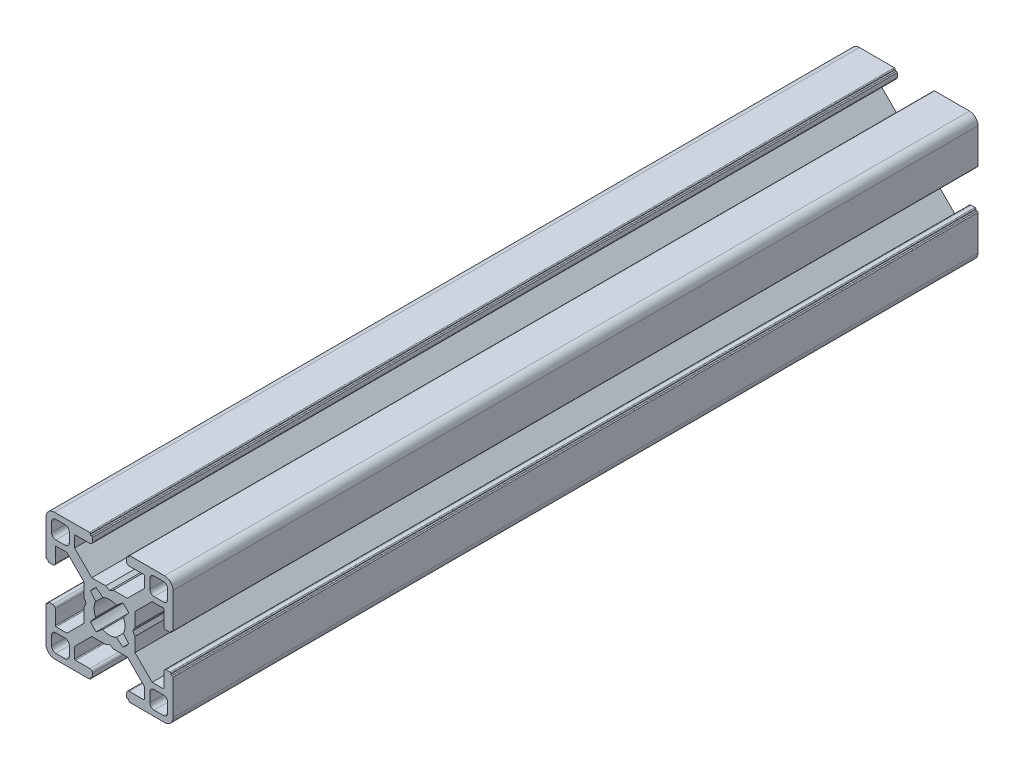
SolidWorks part; units mm, degrees
ref_plane "Front" through (0, 0, 0) normal (0, 0, 1) x (1, 0, 0)
ref_plane "Top" through (0, 0, 0) normal (0, 1, 0) x (1, 0, 0)
ref_plane "Right" through (0, 0, 0) normal (1, 0, 0) x (0, 0, -1)
sketch "Sketch1" plane through (0, 0, 0) normal (0, 0, 1) x (1, 0, 0)
  line L0 (13.7, 12.7) -> (13.7, 10.5)
  line L1 (10.5, 9.5) -> (12.7, 9.5)
  line L2 (9.5, 12.7) -> (9.5, 10.5)
  line L3 (10.5, 13.7) -> (12.7, 13.7)
  line L4 (3.1359, 4.5184) -> (1.6001, 3.2806)
  line L5 (3.2806, 1.6001) -> (4.5053, 3.1547)
  line L6 (6.0045, 0.9) -> (5.4849, 0)
  line L7 (6.0045, 4.2045) -> (6.0045, 0.9)
  line L8 (0, -5.4849) -> (0.9, -6)
  line L9 (0.9, -6) -> (4.2045, -6)
  line L10 (4.2045, -6) -> (8.25, -10.05)
  line L11 (8.25, -10.05) -> (8.25, -12.6)
  line L12 (4.65, -12.8) -> (8.05, -12.8)
  line L13 (4.05, -14.3) -> (4.05, -13.4)
  line L14 (4.25, -14.5) -> (4.35, -14.5)
  line L15 (4.55, -14.8) -> (4.55, -14.7)
  line L16 (4.75, -15) -> (13, -15)
  line L17 (15, -13) -> (15, -4.75)
  line L18 (14.7, -4.55) -> (14.8, -4.55)
  line L19 (14.5, -4.35) -> (14.5, -4.25)
  line L20 (13.4, -4.05) -> (14.3, -4.05)
  line L21 (12.8, -8.05) -> (12.8, -4.65)
  line L22 (12.6, -8.25) -> (10.05, -8.25)
  line L23 (10.05, -8.25) -> (6.0045, -4.2045)
  line L24 (6.0045, -4.2045) -> (6.0045, -0.9)
  line L25 (6.0045, -0.9) -> (5.4849, 0)
  line L26 (10.05, 8.25) -> (6.0045, 4.2045)
  line L27 (12.6, 8.25) -> (10.05, 8.25)
  line L28 (12.8, 8.05) -> (12.8, 4.65)
  line L29 (13.4, 4.05) -> (14.3, 4.05)
  line L30 (14.5, 4.35) -> (14.5, 4.25)
  line L31 (14.7, 4.55) -> (14.8, 4.55)
  line L32 (15, 13) -> (15, 4.75)
  line L33 (4.75, 15) -> (13, 15)
  line L34 (4.55, 14.8) -> (4.55, 14.7)
  line L35 (4.25, 14.5) -> (4.35, 14.5)
  line L36 (4.05, 14.3) -> (4.05, 13.4)
  line L37 (4.65, 12.8) -> (8.05, 12.8)
  line L38 (8.25, 10.05) -> (8.25, 12.6)
  line L39 (4.2045, 6) -> (8.25, 10.05)
  line L40 (0.9, 6) -> (4.2045, 6)
  line L41 (0, 5.4849) -> (0.9, 6)
  line L42 (-13.7, -12.7) -> (-13.7, -10.5)
  line L43 (-10.5, -9.5) -> (-12.7, -9.5)
  line L44 (-9.5, -12.7) -> (-9.5, -10.5)
  line L45 (-10.5, -13.7) -> (-12.7, -13.7)
  line L46 (-3.1359, -4.5184) -> (-1.6001, -3.2806)
  line L47 (-3.2806, -1.6001) -> (-4.5053, -3.1547)
  line L48 (0, 5.4849) -> (-0.9, 6)
  line L49 (-0.9, 6) -> (-4.2045, 6)
  line L50 (-4.2045, 6) -> (-8.25, 10.05)
  line L51 (-8.25, 10.05) -> (-8.25, 12.6)
  line L52 (-4.65, 12.8) -> (-8.05, 12.8)
  line L53 (-4.05, 14.3) -> (-4.05, 13.4)
  line L54 (-4.25, 14.5) -> (-4.35, 14.5)
  line L55 (-4.55, 14.8) -> (-4.55, 14.7)
  line L56 (-4.75, 15) -> (-13, 15)
  line L57 (-15, 13) -> (-15, 4.75)
  line L58 (-14.7, 4.55) -> (-14.8, 4.55)
  line L59 (-14.5, 4.35) -> (-14.5, 4.25)
  line L60 (-13.4, 4.05) -> (-14.3, 4.05)
  line L61 (-12.8, 8.05) -> (-12.8, 4.65)
  line L62 (-12.6, 8.25) -> (-10.05, 8.25)
  line L63 (-10.05, 8.25) -> (-6.0045, 4.2045)
  line L64 (-6.0045, -0.9) -> (-5.4849, 0)
  line L65 (-6.0045, -4.2045) -> (-6.0045, -0.9)
  line L66 (-10.05, -8.25) -> (-6.0045, -4.2045)
  line L67 (-12.6, -8.25) -> (-10.05, -8.25)
  line L68 (-12.8, -8.05) -> (-12.8, -4.65)
  line L69 (-13.4, -4.05) -> (-14.3, -4.05)
  line L70 (-14.5, -4.35) -> (-14.5, -4.25)
  line L71 (-14.7, -4.55) -> (-14.8, -4.55)
  line L72 (-15, -13) -> (-15, -4.75)
  line L73 (-4.75, -15) -> (-13, -15)
  line L74 (-4.55, -14.8) -> (-4.55, -14.7)
  line L75 (-4.25, -14.5) -> (-4.35, -14.5)
  line L76 (-4.05, -14.3) -> (-4.05, -13.4)
  line L77 (3.2806, -1.6001) -> (4.5053, -3.1547)
  line L78 (3.1359, -4.5184) -> (1.6001, -3.2806)
  line L79 (-4.65, -12.8) -> (-8.05, -12.8)
  line L80 (-8.25, -10.05) -> (-8.25, -12.6)
  line L81 (-4.2045, -6) -> (-8.25, -10.05)
  line L82 (-0.9, -6) -> (-4.2045, -6)
  line L83 (0, -5.4849) -> (-0.9, -6)
  line L84 (10.5, -13.7) -> (12.7, -13.7)
  line L85 (9.5, -12.7) -> (9.5, -10.5)
  line L86 (10.5, -9.5) -> (12.7, -9.5)
  line L87 (13.7, -12.7) -> (13.7, -10.5)
  line L88 (-6.0045, 4.2045) -> (-6.0045, 0.9)
  line L89 (-6.0045, 0.9) -> (-5.4849, 0)
  line L90 (-3.2806, 1.6001) -> (-4.5053, 3.1547)
  line L91 (-3.1359, 4.5184) -> (-1.6001, 3.2806)
  line L92 (-10.5, 13.7) -> (-12.7, 13.7)
  line L93 (-9.5, 12.7) -> (-9.5, 10.5)
  line L94 (-10.5, 9.5) -> (-12.7, 9.5)
  line L95 (-13.7, 12.7) -> (-13.7, 10.5)
  line L96 (-23.4857, 0) -> (20.9308, 0) construction
  line L97 (0, 17.9563) -> (0, -17.361) construction
  arc A0 (13.7, 12.7) -> (12.7, 13.7) centre (12.7, 12.7) ccw
  arc A1 (12.7, 9.5) -> (13.7, 10.5) centre (12.7, 10.5) ccw
  arc A2 (9.5, 10.5) -> (10.5, 9.5) centre (10.5, 10.5) ccw
  arc A3 (10.5, 13.7) -> (9.5, 12.7) centre (10.5, 12.7) ccw
  arc A4 (1.6001, 3.2806) -> (-1.6001, 3.2806) centre (0, 0) ccw
  arc A5 (8.25, -12.6) -> (8.05, -12.8) centre (8.05, -12.6) cw
  arc A6 (4.65, -12.8) -> (4.05, -13.4) centre (4.65, -13.4) ccw
  arc A7 (4.05, -14.3) -> (4.25, -14.5) centre (4.25, -14.3) ccw
  arc A8 (4.35, -14.5) -> (4.55, -14.7) centre (4.35, -14.7) cw
  arc A9 (4.55, -14.8) -> (4.75, -15) centre (4.75, -14.8) ccw
  arc A10 (13, -15) -> (15, -13) centre (13, -13) ccw
  arc A11 (15, -4.75) -> (14.8, -4.55) centre (14.8, -4.75) ccw
  arc A12 (14.7, -4.55) -> (14.5, -4.35) centre (14.7, -4.35) cw
  arc A13 (14.5, -4.25) -> (14.3, -4.05) centre (14.3, -4.25) ccw
  arc A14 (13.4, -4.05) -> (12.8, -4.65) centre (13.4, -4.65) ccw
  arc A15 (12.8, -8.05) -> (12.6, -8.25) centre (12.6, -8.05) cw
  arc A16 (4.5053, 3.1547) -> (3.1359, 4.5184) centre (0, 0) ccw
  arc A17 (12.8, 8.05) -> (12.6, 8.25) centre (12.6, 8.05) ccw
  arc A18 (13.4, 4.05) -> (12.8, 4.65) centre (13.4, 4.65) cw
  arc A19 (14.5, 4.25) -> (14.3, 4.05) centre (14.3, 4.25) cw
  arc A20 (14.7, 4.55) -> (14.5, 4.35) centre (14.7, 4.35) ccw
  arc A21 (15, 4.75) -> (14.8, 4.55) centre (14.8, 4.75) cw
  arc A22 (13, 15) -> (15, 13) centre (13, 13) cw
  arc A23 (4.55, 14.8) -> (4.75, 15) centre (4.75, 14.8) cw
  arc A24 (4.35, 14.5) -> (4.55, 14.7) centre (4.35, 14.7) ccw
  arc A25 (4.05, 14.3) -> (4.25, 14.5) centre (4.25, 14.3) cw
  arc A26 (4.65, 12.8) -> (4.05, 13.4) centre (4.65, 13.4) cw
  arc A27 (8.25, 12.6) -> (8.05, 12.8) centre (8.05, 12.6) ccw
  arc A28 (-13.7, -12.7) -> (-12.7, -13.7) centre (-12.7, -12.7) ccw
  arc A29 (-12.7, -9.5) -> (-13.7, -10.5) centre (-12.7, -10.5) ccw
  arc A30 (-9.5, -10.5) -> (-10.5, -9.5) centre (-10.5, -10.5) ccw
  arc A31 (-10.5, -13.7) -> (-9.5, -12.7) centre (-10.5, -12.7) ccw
  arc A32 (-4.5053, -3.1547) -> (-3.1359, -4.5184) centre (0, 0) ccw
  arc A33 (-3.2806, 1.6001) -> (-3.2806, -1.6001) centre (0, 0) ccw
  arc A34 (-8.25, 12.6) -> (-8.05, 12.8) centre (-8.05, 12.6) cw
  arc A35 (-4.65, 12.8) -> (-4.05, 13.4) centre (-4.65, 13.4) ccw
  arc A36 (-4.05, 14.3) -> (-4.25, 14.5) centre (-4.25, 14.3) ccw
  arc A37 (-4.35, 14.5) -> (-4.55, 14.7) centre (-4.35, 14.7) cw
  arc A38 (-4.55, 14.8) -> (-4.75, 15) centre (-4.75, 14.8) ccw
  arc A39 (-13, 15) -> (-15, 13) centre (-13, 13) ccw
  arc A40 (-15, 4.75) -> (-14.8, 4.55) centre (-14.8, 4.75) ccw
  arc A41 (-14.7, 4.55) -> (-14.5, 4.35) centre (-14.7, 4.35) cw
  arc A42 (-14.5, 4.25) -> (-14.3, 4.05) centre (-14.3, 4.25) ccw
  arc A43 (-13.4, 4.05) -> (-12.8, 4.65) centre (-13.4, 4.65) ccw
  arc A44 (-12.8, 8.05) -> (-12.6, 8.25) centre (-12.6, 8.05) cw
  arc A45 (-4.5053, 3.1547) -> (-3.1359, 4.5184) centre (0, 0) cw
  arc A46 (-12.8, -8.05) -> (-12.6, -8.25) centre (-12.6, -8.05) ccw
  arc A47 (-13.4, -4.05) -> (-12.8, -4.65) centre (-13.4, -4.65) cw
  arc A48 (-14.5, -4.25) -> (-14.3, -4.05) centre (-14.3, -4.25) cw
  arc A49 (3.2806, 1.6001) -> (3.2806, -1.6001) centre (0, 0) cw
  arc A50 (4.5053, -3.1547) -> (3.1359, -4.5184) centre (0, 0) cw
  arc A51 (1.6001, -3.2806) -> (-1.6001, -3.2806) centre (0, 0) cw
  arc A52 (-14.7, -4.55) -> (-14.5, -4.35) centre (-14.7, -4.35) ccw
  arc A53 (-15, -4.75) -> (-14.8, -4.55) centre (-14.8, -4.75) cw
  arc A54 (-13, -15) -> (-15, -13) centre (-13, -13) cw
  arc A55 (-4.55, -14.8) -> (-4.75, -15) centre (-4.75, -14.8) cw
  arc A56 (10.5, -13.7) -> (9.5, -12.7) centre (10.5, -12.7) cw
  arc A57 (9.5, -10.5) -> (10.5, -9.5) centre (10.5, -10.5) cw
  arc A58 (12.7, -9.5) -> (13.7, -10.5) centre (12.7, -10.5) cw
  arc A59 (13.7, -12.7) -> (12.7, -13.7) centre (12.7, -12.7) cw
  arc A60 (-4.35, -14.5) -> (-4.55, -14.7) centre (-4.35, -14.7) ccw
  arc A61 (-4.05, -14.3) -> (-4.25, -14.5) centre (-4.25, -14.3) cw
  arc A62 (-4.65, -12.8) -> (-4.05, -13.4) centre (-4.65, -13.4) cw
  arc A63 (-8.25, -12.6) -> (-8.05, -12.8) centre (-8.05, -12.6) ccw
  arc A64 (-10.5, 13.7) -> (-9.5, 12.7) centre (-10.5, 12.7) cw
  arc A65 (-9.5, 10.5) -> (-10.5, 9.5) centre (-10.5, 10.5) cw
  arc A66 (-12.7, 9.5) -> (-13.7, 10.5) centre (-12.7, 10.5) cw
  arc A67 (-13.7, 12.7) -> (-12.7, 13.7) centre (-12.7, 12.7) cw
  point P81 (15, 15)
  point P82 (0, 15)
  point P203 (0, -15)
  point P204 (15, -15)
  point P206 (0, 0)
  point P207 (15, 0)
  point P219 (-15, 0)
  point P220 (-15, -15)
  point P221 (-15, 15)
  dimension "D6" = 7.3
  dimension "D7" = 11
  dimension "D1" = 30
  dimension "D2" = 15
  dimension "D3" = 30
  dimension "D4" = 8.1
  dimension "D5" = 9
  dimension "D8" = 8.1
extrude "Base-Extrude" add sketch "Sketch1" against normal blind 190
